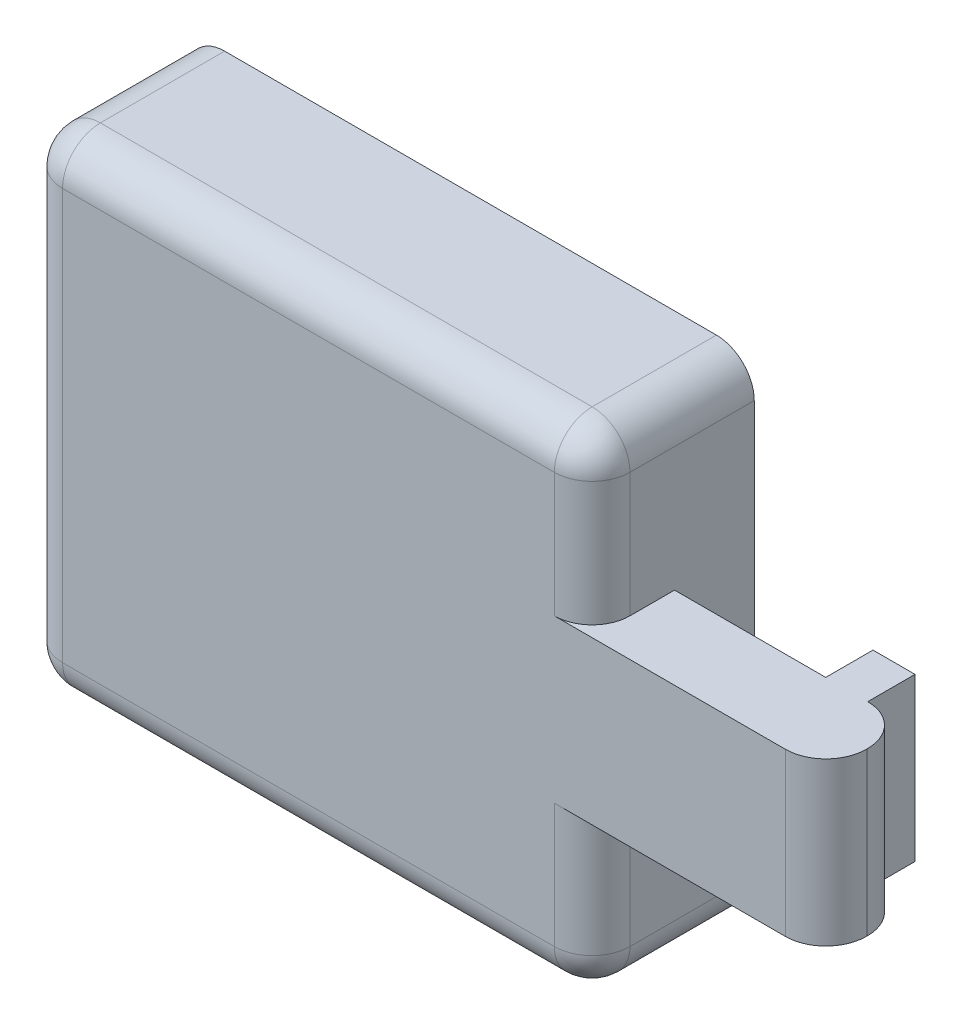
SolidWorks part; units mm, degrees
ref_plane "Front Plane" through (0, 0, 0) normal (0, 0, 1) x (1, 0, 0)
ref_plane "Top Plane" through (0, 0, 0) normal (0, 1, 0) x (1, 0, 0)
ref_plane "Right Plane" through (0, 0, 0) normal (1, 0, 0) x (0, 0, -1)
sketch "Sketch1" plane through (0, 0, 0) normal (0, 0, 1) x (1, 0, 0)
  line L1 (-52.9656, 23.8345) -> (-48.7656, 23.8345)
  line L2 (-52.9656, 23.8345) -> (-52.9656, 20.2345)
  line L3 (-52.9656, 20.2345) -> (-48.7656, 20.2345)
  line L4 (-48.7656, 23.8345) -> (-48.7656, 20.2345)
  dimension "D1" = 3.6
  dimension "D2" = 4.2
extrude "Boss-Extrude1" add sketch "Sketch1" along normal blind 1.2
sketch "Sketch2" plane through (-48.7656, 0, 0) normal (1, 0, 0) x (0, 0, -1)
  line L1 (-0.59, 22.6345) -> (-1.2, 22.6345)
  line L2 (-0.59, 22.6345) -> (-0.59, 21.4345)
  line L3 (-0.59, 21.4345) -> (-1.2, 21.4345)
  line L4 (-1.2, 22.6345) -> (-1.2, 21.4345)
  line L5 (-1.2, 20.2345) -> (-1.2, 23.8345) construction
  line L6 (-1.2, 20.2345) -> (0, 20.2345) construction
  point P10 (0, 21.4345)
  point P11 (0, 0)
  dimension "D1" = 1.2
  dimension "D2" = 1.2
  dimension "D3" = 0.61
extrude "Boss-Extrude2" add sketch "Sketch2" along normal blind 1.73
fillet "Fillet6" radius 0.28 9 edges at (-52.9656, 20.2345, 0.6) (-52.9656, 23.8345, 0.6) (-48.7656, 23.8345, 0.6) (-48.7656, 20.2345, 0.6) (-48.7656, 23.2345, 1.2) (-48.7656, 20.8345, 1.2) (-50.8656, 23.8345, 1.2) (-50.8656, 20.2345, 1.2) (-52.9656, 22.0345, 1.2)
fillet "Fillet8" radius 0.3 2 edges at (-47.0356, 22.0345, 0.59) (-47.0356, 22.0345, 1.2)
sketch "Sketch8" plane through (0, 0, 0.59) normal (0, 0, -1) x (-1, 0, 0)
  line L0 (47.3356, 21.4345) -> (48.7656, 21.4345) construction
  line L1 (47.3356, 22.6345) -> (47.6467, 22.6345)
  line L2 (47.3356, 22.6345) -> (47.3356, 21.4345)
  line L3 (47.3356, 21.4345) -> (47.6467, 21.4345)
  line L4 (47.6467, 22.6345) -> (47.6467, 21.4345)
  dimension "D1" = 1.2
  dimension "D2" = 0.3111
extrude "Boss-Extrude3" add sketch "Sketch8" along normal blind 0.35
